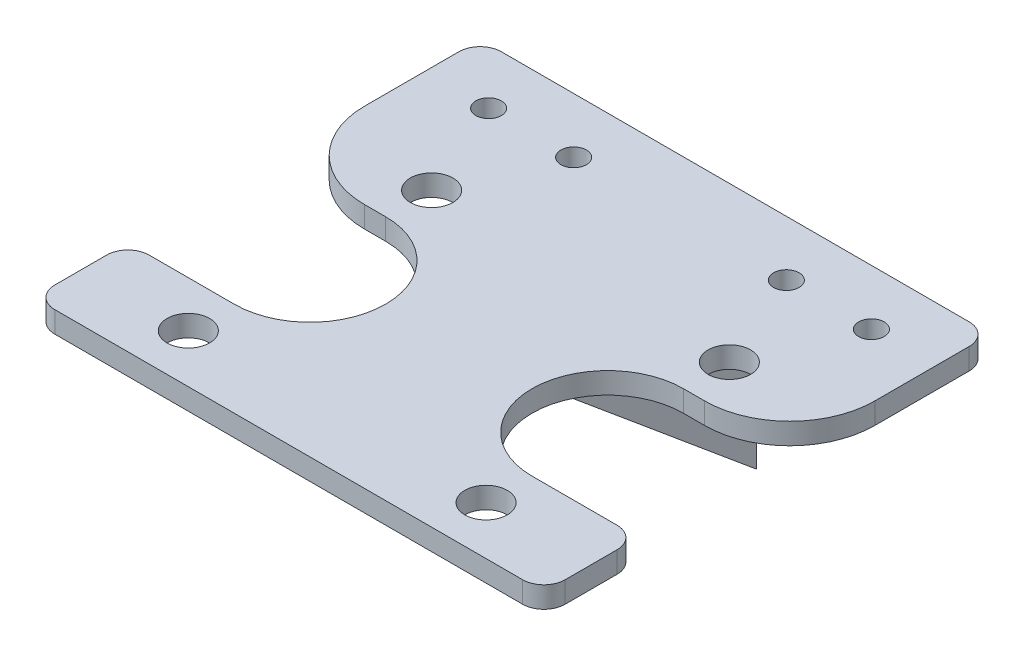
SolidWorks part; units mm, degrees
material "6061-T6 (SS)"
ref_plane "Front Plane" through (0, 0, 0) normal (0, 0, 1) x (1, 0, 0)
ref_plane "Top Plane" through (0, 0, 0) normal (0, 1, 0) x (1, 0, 0)
ref_plane "Right Plane" through (0, 0, 0) normal (1, 0, 0) x (0, 0, -1)
sketch "Sketch1" plane through (0, 0, 0) normal (0, 1, 0) x (1, 0, 0)
  line L0 (60, 2.8) -> (60, 50)
  line L1 (-60, -55) -> (60, -55)
  line L2 (-35, -32.8) -> (-60, -32.8)
  line L3 (60, 50) -> (-60, 50)
  line L4 (-60, 50) -> (-60, 2.8)
  line L5 (60, -55) -> (60, -32.8)
  line L6 (-35, 2.8) -> (-60, 2.8)
  line L7 (-60, -32.8) -> (-60, -55)
  line L8 (60, -32.8) -> (35, -32.8)
  line L9 (60, 2.8) -> (35, 2.8)
  arc A0 (-35, -32.8) -> (-35, 2.8) centre (-35, -15) ccw
  arc A1 (35, 2.8) -> (35, -32.8) centre (35, -15) ccw
  circle A2 centre (-35, 13.6) radius 5
  circle A3 centre (-35, -43.6) radius 5
  circle A4 centre (35, 13.6) radius 5
  circle A5 centre (35, -43.6) radius 5
  circle A6 centre (-45, 37) radius 3
  circle A7 centre (-25, 37) radius 3
  circle A8 centre (25, 37) radius 3
  circle A9 centre (45, 37) radius 3
  point P0 (15, -15)
  point P5 (0.4714, 24.3506)
  point P27 (0, -30)
  point P32 (0, 50)
  dimension "D2" = 35.6
  dimension "D4" = 35.6
  dimension "D6" = 10
  dimension "D16" = 40
  dimension "D14" = 6
  dimension "D17" = 6
  dimension "D18" = 6
  dimension "D19" = 6
  dimension "D7" = 28.6
  dimension "D8" = 28.6
  dimension "D10" = 28.6
  dimension "D11" = 28.6
  dimension "D13" = 65
  dimension "D20" = 20
  dimension "D21" = 20
  dimension "D22" = 13
  dimension "D23" = 10
  dimension "D24" = 35
  dimension "D25" = 120
  dimension "D26" = 10
  dimension "D27" = 35
extrude "Boss-Extrude2" add sketch "Sketch1" against normal blind 5
sketch "Sketch2" plane through (0, 0, 0) normal (1, 0, 0) x (0, 0, -1)
  line L0 (-10, -5) -> (50, -55)
  line L1 (50, -5) -> (2.8, -5) construction
  line L2 (50, -55) -> (50, -5)
  line L3 (50, -5) -> (-10, -5)
  dimension "D1" = 50
  dimension "D2" = 60
extrude "Boss-Extrude3" add sketch "Sketch2" along normal mid plane 10
fillet "Fillet1" radius 20 2 edges at (60, -2.5, -2.8) (-60, -2.5, -2.8)
fillet "Fillet2" radius 5 6 edges at (-60, -2.5, 55) (60, -2.5, 55) (60, -2.5, 32.8) (-60, -2.5, 32.8) (60, -2.5, -50) (-60, -2.5, -50)
